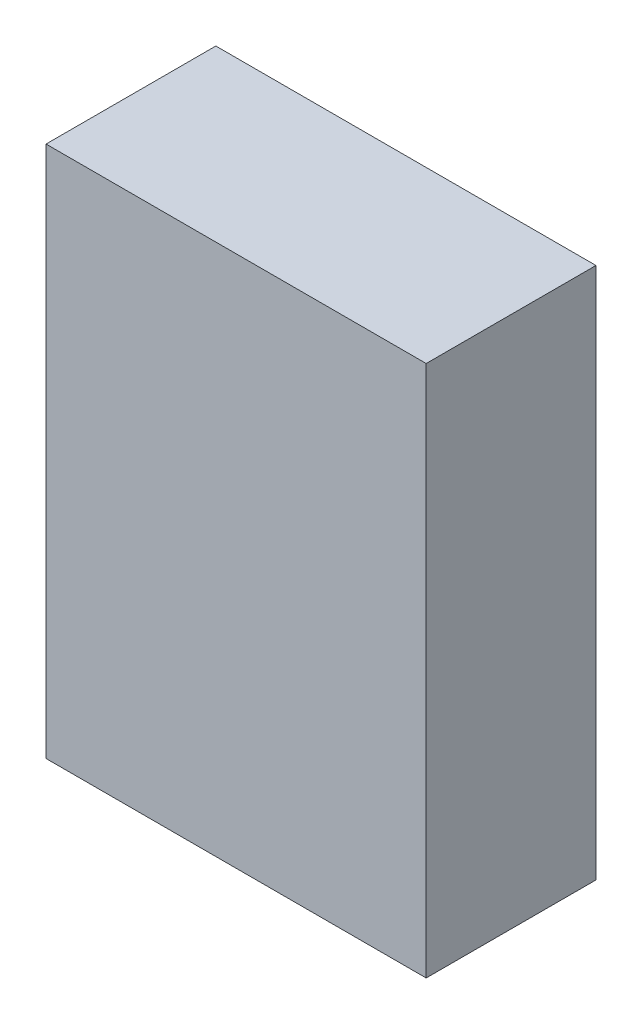
SolidWorks part; units mm, degrees
material "pm"
ref_plane "Front Plane" through (0, 0, 0) normal (0, 0, 1) x (1, 0, 0)
ref_plane "Top Plane" through (0, 0, 0) normal (0, 1, 0) x (1, 0, 0)
ref_plane "Right Plane" through (0, 0, 0) normal (1, 0, 0) x (0, 0, -1)
sketch "Sketch1" plane through (0, 0, 0) normal (1, 0, 0) x (0, 0, -1)
  line L1 (0, 0) -> (67, 0)
  line L2 (0, 0) -> (0, 210)
  line L3 (0, 210) -> (67, 210)
  line L4 (67, 0) -> (67, 210)
  dimension "D1" = 210
  dimension "D2" = 67
extrude "Boss-Extrude1" add sketch "Sketch1" along normal blind 150
